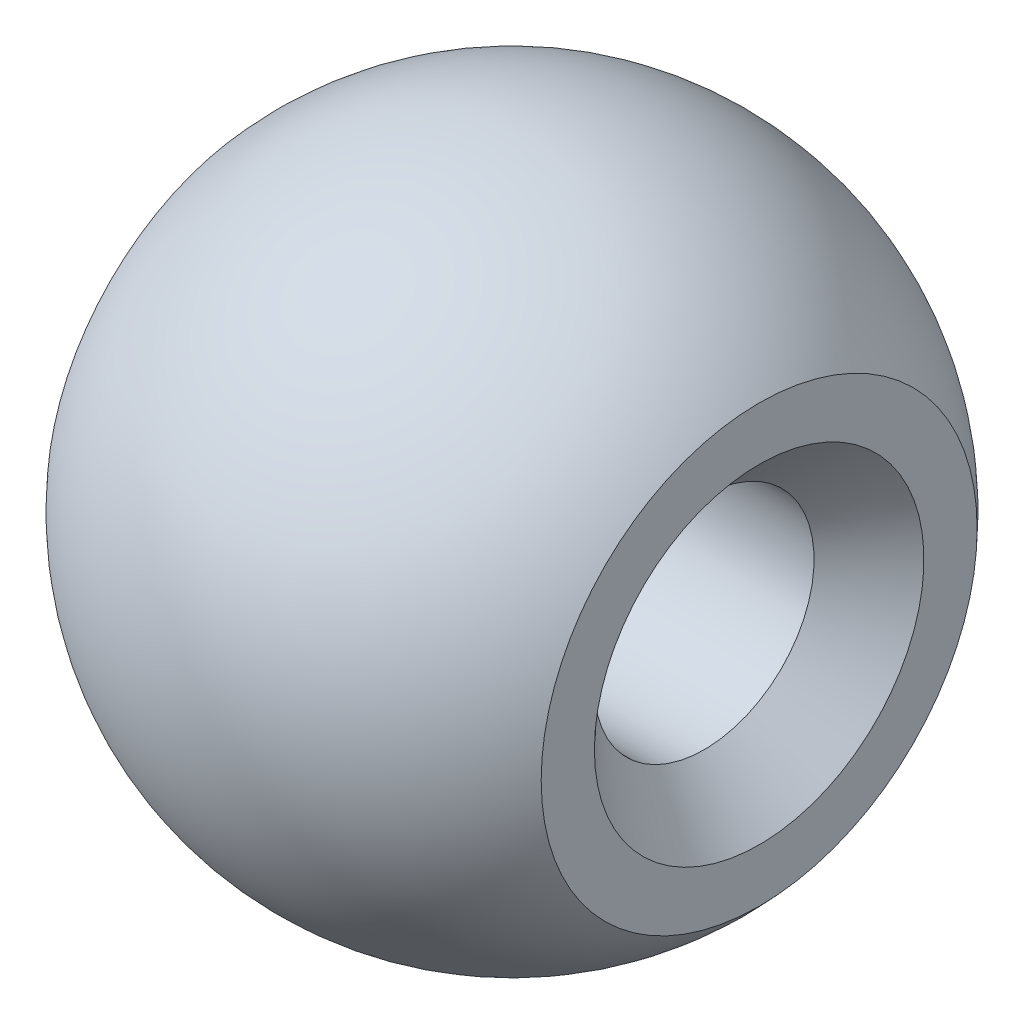
SolidWorks part; units mm, degrees
ref_plane "Front Plane" through (0, 0, 0) normal (0, 0, 1) x (1, 0, 0)
ref_plane "Top Plane" through (0, 0, 0) normal (0, 1, 0) x (1, 0, 0)
ref_plane "Right Plane" through (0, 0, 0) normal (1, 0, 0) x (0, 0, -1)
sketch "Sketch2" plane through (0, 0, 0) normal (0, 0, 1) x (1, 0, 0)
  line L2 (4.5, 3.9686) -> (-4.5, 3.9686)
  line L3 (-6, 0) -> (6, 0) construction
  line L6 (6, 0) -> (-6, 0) construction
  line L7 (4.5, 3.9686) -> (4.5, 3)
  line L8 (-4.5, 3.9686) -> (-4.5, 2)
  line L9 (3.5, 2) -> (-4.5, 2)
  line L11 (3.5, 2) -> (4.5, 3)
  arc A1 (4.5, 3.9686) -> (-4.5, 3.9686) centre (0, 0) ccw
  dimension "D1" = 12
  dimension "D2" = 9
  dimension "D3" = 2
  dimension "D4" = 1
  dimension "D5" = 45
revolve "Revolve1" add sketch "Sketch2" angle 360 about L3
